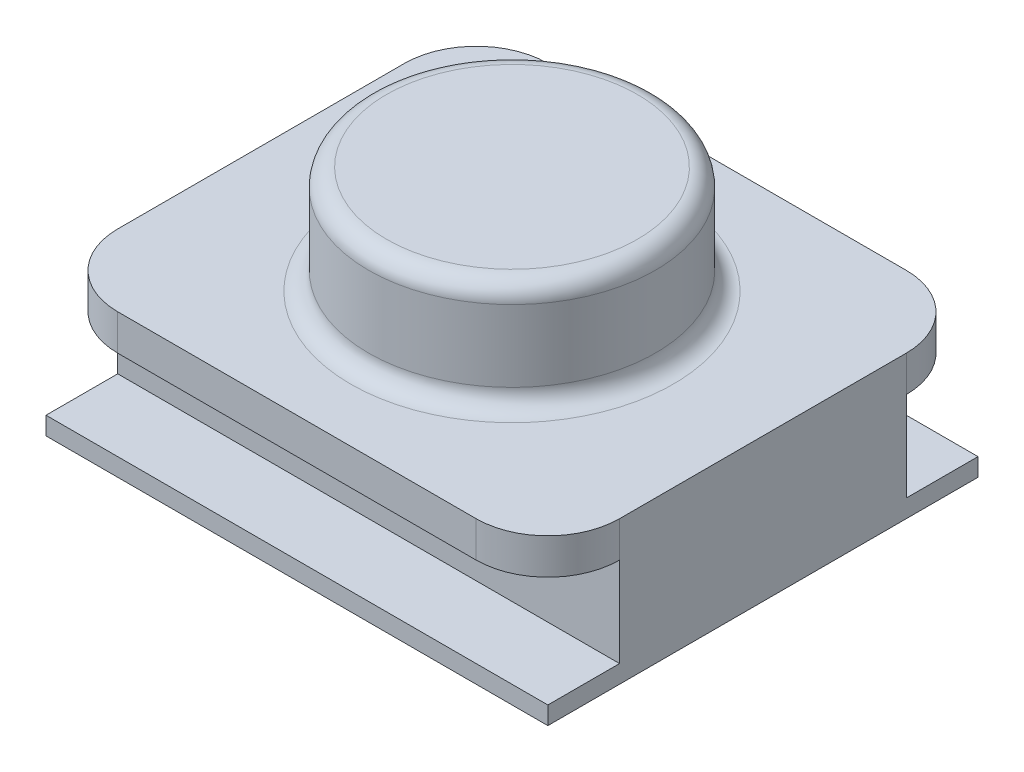
SolidWorks part; units mm, degrees
material "PP Kopolimer"
ref_plane "Front Plane" through (0, 0, 0) normal (0, 0, 1) x (1, 0, 0)
ref_plane "Top Plane" through (0, 0, 0) normal (0, 1, 0) x (1, 0, 0)
ref_plane "Right Plane" through (0, 0, 0) normal (1, 0, 0) x (0, 0, -1)
sketch "Szkic1" plane through (0, 0, 0) normal (0, 1, 0) x (1, 0, 0)
  line L1 (-3.5, -3) -> (3.5, -3)
  line L2 (-3.5, -3) -> (-3.5, 3)
  line L3 (-3.5, 3) -> (3.5, 3)
  line L4 (3.5, -3) -> (3.5, 3)
  dimension "D1" = 6
  dimension "D2" = 7
extrude "Dodanie-wyciągnięcie1" add sketch "Szkic1" along normal blind 0.25
sketch "Szkic2" plane through (0, 0.25, 0) normal (0, 1, 0) x (1, 0, 0)
  line L1 (-3.5, -2) -> (3.5, -2)
  line L2 (-3.5, -2) -> (-3.5, 2)
  line L3 (-3.5, 2) -> (3.5, 2)
  line L4 (3.5, -2) -> (3.5, 2)
extrude "Dodanie-wyciągnięcie2" add sketch "Szkic2" along normal blind 1.25
sketch "Szkic3" plane through (0, 1.5, 0) normal (0, 1, 0) x (1, 0, 0)
  line L1 (-3.5, 3) -> (3.5, 3)
  line L2 (-3.5, 3) -> (-3.5, -3)
  line L3 (-3.5, -3) -> (3.5, -3)
  line L4 (3.5, 3) -> (3.5, -3)
extrude "Dodanie-wyciągnięcie3" add sketch "Szkic3" along normal blind 0.5
sketch "Szkic4" plane through (0, 2, 0) normal (0, 1, 0) x (1, 0, 0)
  circle A0 centre (0, 0) radius 2
extrude "Dodanie-wyciągnięcie4" add sketch "Szkic4" along normal blind 1.5
fillet "Zaokrąglenie1" radius 0.25 2 edges at (0, 2, 2) (0, 3.5, 2)
fillet "Zaokrąglenie2" radius 1 4 edges at (-3.5, 1.75, -3) (3.5, 1.75, -3) (3.5, 1.75, 3) (-3.5, 1.75, 3)
sketch "Szkic5" plane through (0, 0, 0) normal (0, -1, 0) x (1, 0, 0)
  line L1 (-2, 0.5) -> (2, 0.5)
  line L2 (-2, 0.5) -> (-2, -0.5)
  line L3 (-2, -0.5) -> (2, -0.5)
  line L4 (2, 0.5) -> (2, -0.5)
extrude "Dodanie-wyciągnięcie5" add sketch "Szkic5" along normal blind 1
sketch "Szkic6" plane through (0, 0, -0.5) normal (0, 0, -1) x (-1, 0, 0)
  line L0 (0, 0) -> (0, -0.25) construction
  line L1 (0, -0.25) -> (0, -0.5) construction
  line L3 (1, -0.5) -> (-1, -0.5)
  line L4 (1, -0.5) -> (1, -0.25)
  line L5 (1, -0.25) -> (-1, -0.25)
  line L6 (-1, -0.5) -> (-1, -0.25)
extrude "Wytnij-wyciągnięcie1" cut sketch "Szkic6" against normal blind 1
